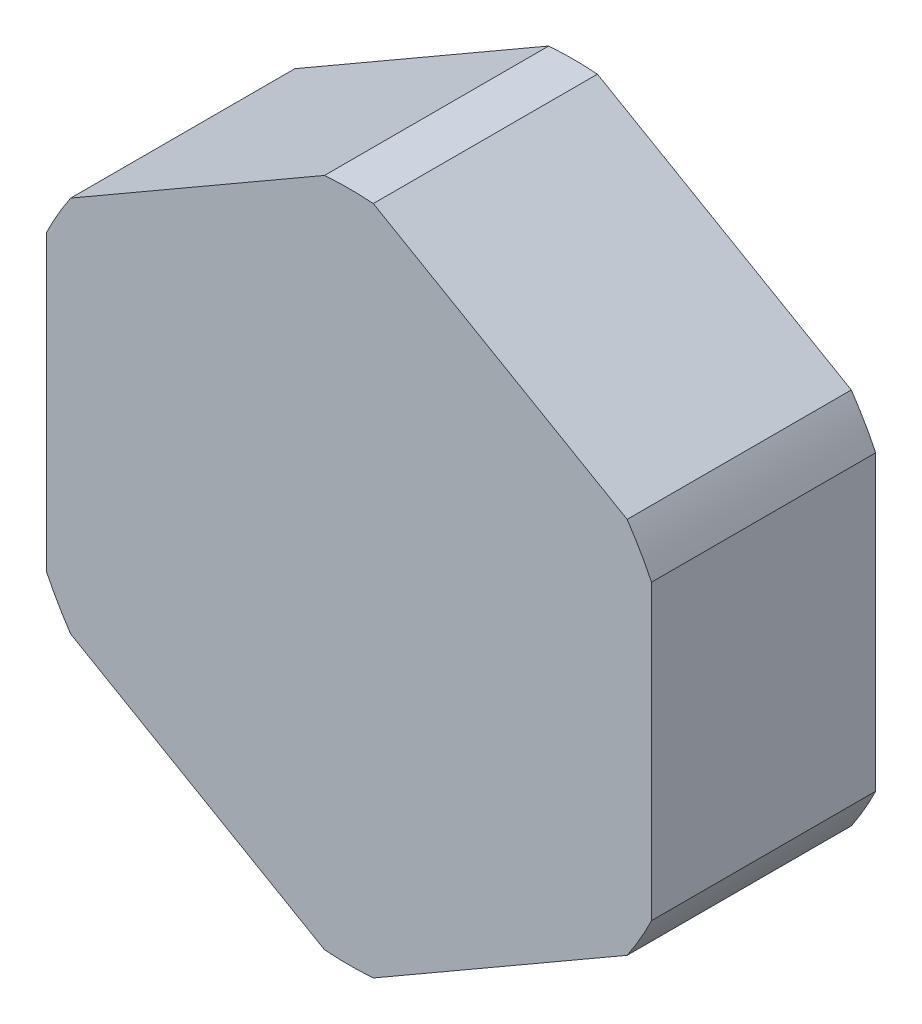
SolidWorks part; units mm, degrees
material "Латунь"
ref_plane "Front" through (0, 0, 0) normal (0, 0, 1) x (1, 0, 0)
ref_plane "Top" through (0, 0, 0) normal (0, 1, 0) x (1, 0, 0)
ref_plane "Right" through (0, 0, 0) normal (1, 0, 0) x (0, 0, -1)
sketch "Эскиз1" plane through (0, 0, 0) normal (0, 0, 1) x (1, 0, 0)
  line L1 (0, 15.5885) -> (-13.5, 7.7942)
  line L2 (-13.5, 7.7942) -> (-13.5, -7.7942)
  line L3 (-13.5, -7.7942) -> (0, -15.5885)
  line L4 (0, -15.5885) -> (13.5, -7.7942)
  line L5 (13.5, -7.7942) -> (13.5, 7.7942)
  line L6 (13.5, 7.7942) -> (0, 15.5885)
  circle A0 centre (0, 0) radius 15
  circle A1 centre (0, 0) radius 13.5 construction
  dimension "D1" = 30
  dimension "D2" = 27
extrude "Бобышка-Вытянуть1" add sketch "Эскиз1" along normal blind 10 contours L5 A0 L6 L1 L2 L3 L4
